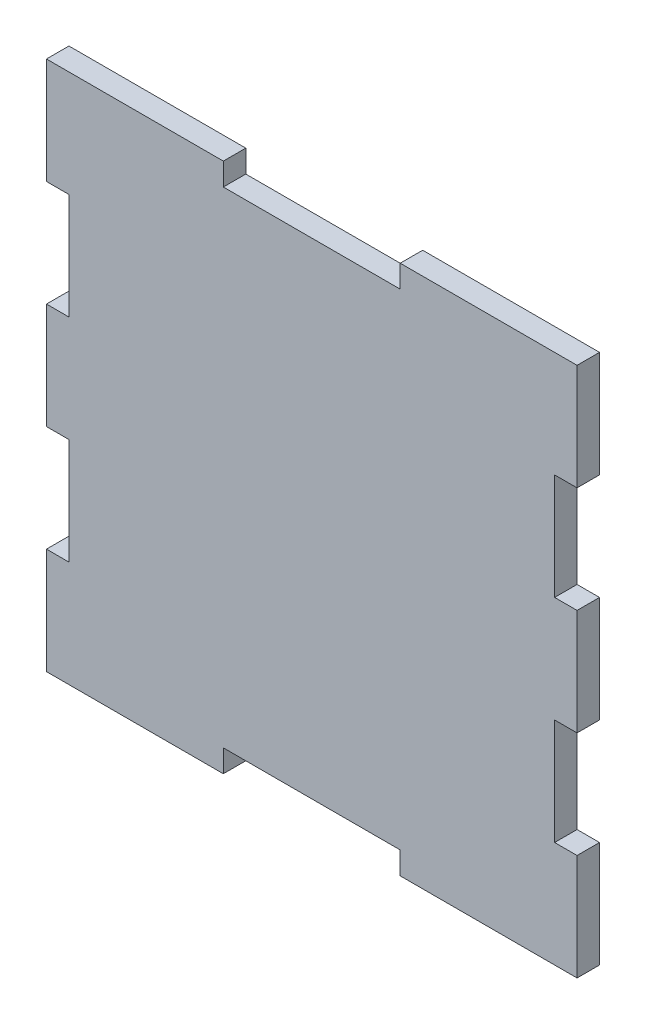
SolidWorks part; units mm, degrees
ref_plane "Front Plane" through (0, 0, 0) normal (0, 0, 1) x (1, 0, 0)
ref_plane "Top Plane" through (0, 0, 0) normal (0, 1, 0) x (1, 0, 0)
ref_plane "Right Plane" through (0, 0, 0) normal (1, 0, 0) x (0, 0, -1)
sketch "Sketch2" plane through (0, 0, 0) normal (0, 0, 1) x (1, 0, 0)
  line L0 (-7.2056, 187.8918) -> (-7.2056, 157.8918)
  line L1 (-0.8556, 67.8918) -> (-7.2056, 67.8918)
  line L2 (-7.2056, 67.8918) -> (-7.2056, 37.8918)
  line L3 (-7.2056, 157.8918) -> (-0.8556, 157.8918)
  line L4 (67.7944, 94.2853) -> (67.7944, 207.1222) construction
  line L5 (-7.2056, 187.8918) -> (42.7944, 187.8918)
  line L6 (42.7944, 187.8918) -> (42.7944, 181.5418)
  line L7 (42.7944, 181.5418) -> (92.7944, 181.5418)
  line L8 (92.7944, 181.5418) -> (92.7944, 187.8918)
  line L9 (92.7944, 187.8918) -> (142.7944, 187.8918)
  line L10 (142.7944, 67.8918) -> (142.7944, 37.8918)
  line L11 (136.4444, 67.8918) -> (142.7944, 67.8918)
  line L12 (136.4444, 97.8918) -> (136.4444, 67.8918)
  line L13 (142.7944, 97.8918) -> (136.4444, 97.8918)
  line L14 (-0.8556, 157.8918) -> (-0.8556, 127.8918)
  line L15 (-0.8556, 127.8918) -> (-7.2056, 127.8918)
  line L16 (-7.2056, 127.8918) -> (-7.2056, 97.8918)
  line L17 (-7.2056, 97.8918) -> (-0.8556, 97.8918)
  line L18 (-0.8556, 97.8918) -> (-0.8556, 67.8918)
  line L19 (142.7944, 127.8918) -> (142.7944, 97.8918)
  line L20 (136.4444, 127.8918) -> (142.7944, 127.8918)
  line L21 (136.4444, 157.8918) -> (136.4444, 127.8918)
  line L22 (142.7944, 157.8918) -> (136.4444, 157.8918)
  line L23 (142.7944, 187.8918) -> (142.7944, 157.8918)
  line L24 (-7.2056, 37.8918) -> (42.7944, 37.8918)
  line L25 (42.7944, 37.8918) -> (42.7944, 44.2418)
  line L26 (42.7944, 44.2418) -> (92.7944, 44.2418)
  line L27 (92.7944, 44.2418) -> (92.7944, 37.8918)
  line L28 (92.7944, 37.8918) -> (142.7944, 37.8918)
  point P4 (0, 0)
  dimension "D4" = 30
  dimension "D6" = 50
  dimension "D11" = 30
  dimension "D3" = 30
  dimension "D5" = 50
  dimension "D8" = 6.35
  dimension "D9" = 6.35
  dimension "D12" = 30
  dimension "D13" = 30
  dimension "D14" = 6.35
  dimension "D15" = 6.35
extrude "Boss-Extrude1" add sketch "Sketch2" along normal blind 6.35
